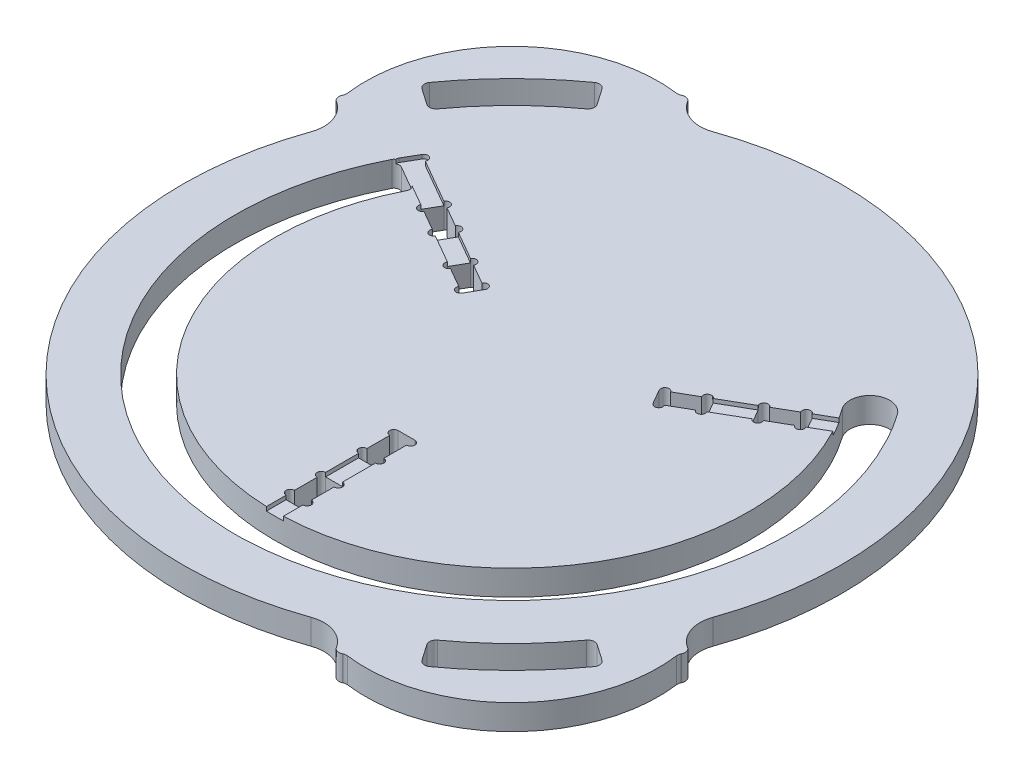
SolidWorks part; units mm, degrees
ref_plane "Front Plane" through (0, 0, 0) normal (0, 0, 1) x (1, 0, 0)
ref_plane "Top Plane" through (0, 0, 0) normal (0, 1, 0) x (1, 0, 0)
ref_plane "Right Plane" through (0, 0, 0) normal (1, 0, 0) x (0, 0, -1)
sketch "Sketch1" plane through (0, 0, 0) normal (0, 1, 0) x (1, 0, 0)
  line L0 (0, 0) -> (0, 240) construction
  line L1 (0, 0) -> (207.8461, 120) construction
  line L2 (0, 0) -> (-207.8461, 120) construction
  line L3 (147.0652, 103.7875) -> (173.1383, 118.8408) construction
  line L4 (-184.9572, 99.4527) -> (-158.9625, 84.4447)
  line L5 (3.175, -5.4993) -> (211.0211, 114.5007) construction
  line L6 (-3.175, 5.4993) -> (204.6711, 125.4993) construction
  line L7 (0, 250) -> (-250, 250) construction
  line L8 (-250, 250) -> (-250, 0) construction
  line L9 (-250, 0) -> (0, 0) construction
  line L10 (0, 0) -> (-176.7767, 176.7767) construction
  line L11 (-176.7767, 176.7767) -> (-250, 250) construction
  line L12 (0, 0) -> (-250, 114.5644) construction
  line L13 (0, 0) -> (-114.5644, 250) construction
  line L14 (0, 0) -> (-156.4996, 226.1258) construction
  line L15 (0, 0) -> (-226.1258, 156.4996) construction
  line L16 (-142.2724, 205.5689) -> (-169.7056, 169.7056) construction
  line L17 (-169.7056, 169.7056) -> (-205.5689, 142.2724) construction
  line L18 (-226.1258, 156.4996) -> (-205.5689, 142.2724)
  line L19 (-142.2724, 205.5689) -> (-156.4996, 226.1258)
  line L20 (-227.2727, 104.1494) -> (-250, 114.5644)
  line L21 (-104.1494, 227.2727) -> (-114.5644, 250)
  line L22 (-250, 0) -> (-250, -250) construction
  line L23 (-250, -250) -> (0, -250) construction
  line L24 (-194.4544, 194.4544) -> (-215.6676, 215.6676) construction
  line L25 (0, 0) -> (-250, -250) construction
  line L26 (156.4996, -226.1258) -> (142.2724, -205.5689)
  line L27 (205.5689, -142.2724) -> (226.1258, -156.4996)
  line L28 (227.2727, -104.1494) -> (250, -114.5644)
  line L29 (104.1494, -227.2727) -> (114.5644, -250)
  circle A0 centre (0, 0) radius 230 construction
  circle A1 centre (0, 0) radius 240 construction
  circle A2 centre (0, 0) radius 190 construction
  arc A3 (-158.9625, 84.4447) -> (147.0652, 103.7875) centre (0, 0) ccw
  arc A4 (173.1383, 118.8408) -> (-184.9572, 99.4527) centre (0, 0) cw
  circle A5 centre (160.1017, 111.3141) radius 15.0041 construction
  arc A6 (147.0652, 103.7875) -> (173.1383, 118.8408) centre (160.1017, 111.3141) cw
  circle A7 centre (0, 0) radius 250 construction
  circle A8 centre (0, 0) radius 275 construction
  arc A9 (-176.7767, 176.7767) -> (-142.2724, 205.5689) centre (0, 0) cw
  arc A10 (-176.7767, 176.7767) -> (-205.5689, 142.2724) centre (0, 0) ccw
  arc A11 (-226.1258, 156.4996) -> (-156.4996, 226.1258) centre (0, 0) cw
  circle A12 centre (-137.0838, 137.0838) radius 111.1343 construction
  circle A13 centre (-226.1258, 156.4996) radius 20 construction
  arc A14 (-114.5644, 250) -> (-120.8451, 247.0252) centre (0, 0) ccw
  arc A15 (-120.8451, 247.0252) -> (-247.0252, 120.8451) centre (-137.0838, 137.0838) ccw
  arc A16 (-247.0252, 120.8451) -> (-250, 114.5644) centre (0, 0) ccw
  arc A17 (176.7767, -176.7767) -> (142.2724, -205.5689) centre (0, 0) cw
  arc A18 (176.7767, -176.7767) -> (205.5689, -142.2724) centre (0, 0) ccw
  arc A19 (156.4996, -226.1258) -> (226.1258, -156.4996) centre (0, 0) ccw
  arc A20 (250, -114.5644) -> (247.0252, -120.8451) centre (0, 0) cw
  arc A21 (247.0252, -120.8451) -> (120.8451, -247.0252) centre (137.0838, -137.0838) cw
  arc A22 (120.8451, -247.0252) -> (114.5644, -250) centre (0, 0) cw
  arc A23 (-227.2727, 104.1494) -> (104.1494, -227.2727) centre (0, 0) ccw
  arc A24 (227.2727, -104.1494) -> (-104.1494, 227.2727) centre (0, 0) ccw
  dimension "D1" = 460
  dimension "D2" = 480
  dimension "D3" = 40
  dimension "D6" = 10
  dimension "D7" = 20
  dimension "D12" = 6.35
  dimension "D11" = 10
  dimension "D14" = 25
  dimension "D15" = 90
  dimension "D16" = 40
  dimension "D4" = 60
  dimension "D5" = 60
  dimension "D10" = 10
  dimension "D13" = 45
  dimension "D17" = 30
  dimension "D8" = 6.35
  dimension "D9" = 6.35
extrude "Boss-Extrude1" add sketch "Sketch1" along normal blind 19.05
fillet "Fillet1" radius 4 2 edges at (-158.9625, 9.525, -84.4447) (-184.9572, 9.525, -99.4527)
fillet "Fillet2" radius 5 16 edges at (-114.5644, 9.525, -250) (-120.8451, 9.525, -247.0252) (-250, 9.525, -114.5644) (-247.0252, 9.525, -120.8451) (205.5689, 9.525, 142.2724) (142.2724, 9.525, 205.5689) (156.4996, 9.525, 226.1258) (226.1258, 9.525, 156.4996) (-205.5689, 9.525, -142.2724) (-142.2724, 9.525, -205.5689) (-156.4996, 9.525, -226.1258) (-226.1258, 9.525, -156.4996) (250, 9.525, 114.5644) (247.0252, 9.525, 120.8451) (114.5644, 9.525, 250) (120.8451, 9.525, 247.0252)
fillet "Fillet3" radius 25 4 edges at (-104.1494, 9.525, -227.2727) (-227.2727, 9.525, -104.1494) (104.1494, 9.525, 227.2727) (227.2727, 9.525, 104.1494)
sketch "Sketch3" plane through (0, 19.05, 0) normal (0, 1, 0) x (1, 0, 0)
  line L0 (0, 0) -> (0, -250) construction
  line L1 (0, 0) -> (216.5064, 125) construction
  line L2 (0, 0) -> (0, 250) construction
  line L3 (0, 0) -> (-216.5064, 125) construction
  line L4 (3.2, -5.5426) -> (219.7064, 119.4574) construction
  line L5 (-6.4, 0) -> (-6.4, -250) construction
  line L6 (3.2, 5.5426) -> (-213.3064, 130.5426) construction
  line L7 (-3.2, 5.5426) -> (213.3064, 130.5426) construction
  line L8 (6.4, 0) -> (6.4, -250) construction
  line L9 (-3.2, -5.5426) -> (-219.7064, 119.4574) construction
  line L10 (0, -165) -> (0, -180) construction
  line L11 (-6.4, -135) -> (6.4, -135)
  line L12 (-6.4, -135) -> (-6.4, -165) construction
  line L13 (-6.4, -165) -> (6.4, -165)
  line L14 (6.4, -135) -> (6.4, -165) construction
  line L15 (-6.4, -80) -> (6.4, -80)
  line L16 (-6.4, -80) -> (-6.4, -110) construction
  line L17 (-6.4, -110) -> (6.4, -110)
  line L18 (6.4, -80) -> (6.4, -110) construction
  line L19 (-6.4, -141.4) -> (-6.4, -158.6)
  line L20 (6.4, -141.4) -> (6.4, -158.6)
  line L21 (-6.4, -86.4) -> (-6.4, -103.6)
  line L22 (6.4, -86.4) -> (6.4, -103.6)
  arc A0 (-235.7212, 83.2797) -> (83.2797, -235.7212) centre (0, 0) ccw construction
  arc A1 (235.7212, -83.2797) -> (-83.2797, 235.7212) centre (0, 0) ccw construction
  circle A2 centre (0, 0) radius 80 construction
  arc A3 (-6.4, -135) -> (-6.4, -141.4) centre (-6.4, -138.2) ccw
  arc A4 (-6.4, -158.6) -> (-6.4, -165) centre (-6.4, -161.8) ccw
  arc A5 (-160.7003, 81.089) -> (147.0652, 103.7875) centre (0, 0) ccw construction
  arc A6 (6.4, -141.4) -> (6.4, -135) centre (6.4, -138.2) ccw
  arc A7 (6.4, -165) -> (6.4, -158.6) centre (6.4, -161.8) ccw
  arc A8 (6.4, -110) -> (6.4, -103.6) centre (6.4, -106.8) ccw
  arc A9 (6.4, -86.4) -> (6.4, -80) centre (6.4, -83.2) ccw
  arc A10 (-6.4, -80) -> (-6.4, -86.4) centre (-6.4, -83.2) ccw
  arc A11 (-6.4, -103.6) -> (-6.4, -110) centre (-6.4, -106.8) ccw
  dimension "D6" = 160
  dimension "D7" = 15
  dimension "D8" = 6.4
  dimension "D1" = 60
  dimension "D2" = 120
  dimension "D5" = 30
  dimension "D3" = 6.4
  dimension "D4" = 6.4
extrude "Cut-Extrude1" cut sketch "Sketch3" against normal through all
pattern_circular "CirPattern1" count 3 over 360 about axis through (0, 0, 0) along (0, 1, 0) of "Cut-Extrude1"
sketch "Sketch4" plane through (0, 19.05, 0) normal (0, 1, 0) x (1, 0, 0)
  line L0 (0, 0) -> (181.8653, 105) construction
  line L1 (146.0942, 76.9574) -> (139.6942, 88.0426) construction
  line L2 (3.2, -5.5426) -> (185.0653, 99.4574) construction
  line L3 (-3.2, 5.5426) -> (178.6653, 110.5426) construction
  line L4 (3.2, -5.5426) -> (-3.2, 5.5426) construction
  line L5 (185.0653, 99.4574) -> (178.6653, 110.5426)
  line L6 (66.082, 45.5426) -> (72.482, 34.4574)
  line L7 (72.482, 34.4574) -> (179.5228, 96.2574)
  line L8 (173.1228, 107.3426) -> (66.082, 45.5426)
  arc A1 (178.6653, 110.5426) -> (173.1228, 107.3426) centre (175.8941, 108.9426) ccw
  arc A2 (179.5228, 96.2574) -> (185.0653, 99.4574) centre (182.2941, 97.8574) ccw
  point P8 (142.8942, 82.5)
  dimension "D4" = 6.4
  dimension "D1" = 210
  dimension "D2" = 6.4
  dimension "D3" = 6.4
extrude "Cut-Extrude2" cut sketch "Sketch4" against normal blind 3
pattern_circular "CirPattern2" count 3 over 360 about axis through (0, 0, 0) along (0, 1, 0) of "Cut-Extrude2"
